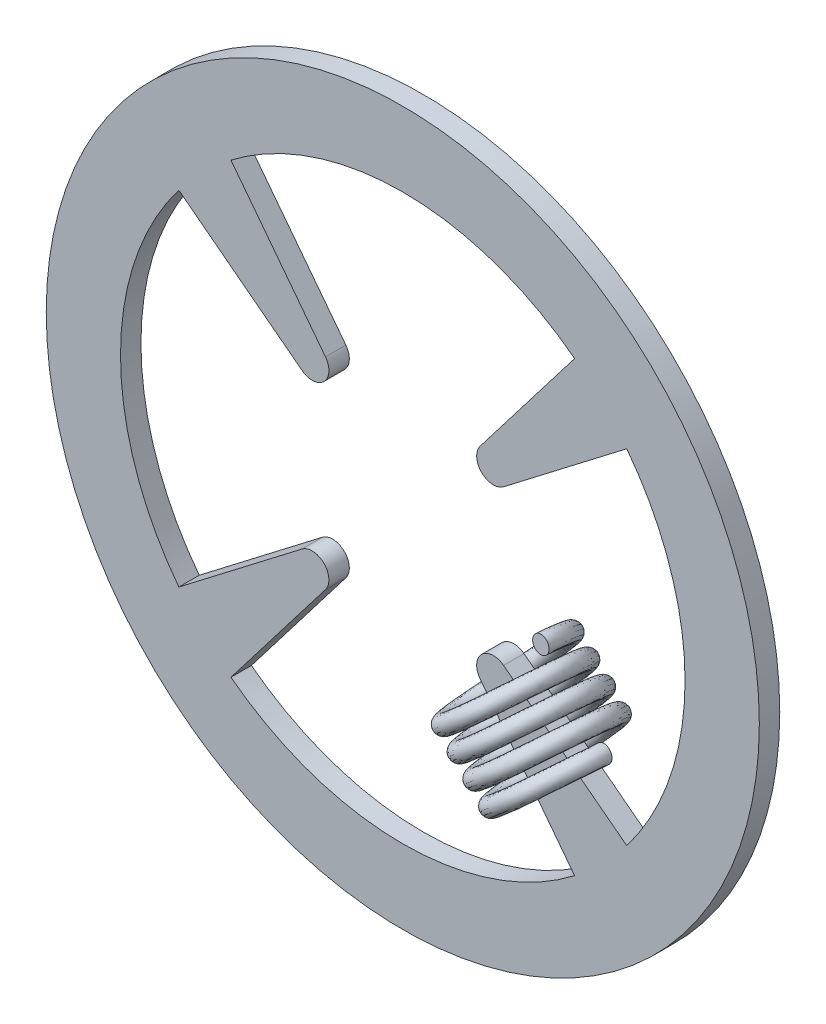
SolidWorks part; units mm, degrees
other "標示1"
sketch "草圖65"
ref_plane "前基準面" through (0, 0, 0) normal (0, 0, 1) x (1, 0, 0)
ref_plane "上基準面" through (0, 0, 0) normal (0, 1, 0) x (1, 0, 0)
ref_plane "右基準面" through (0, 0, 0) normal (1, 0, 0) x (0, 0, -1)
sketch "草圖1" plane through (0, 0, 0) normal (0, 0, 1) x (1, 0, 0)
  circle A0 centre (0, 0) radius 0.96
  circle A1 centre (0, 0) radius 0.76
extrude "填料-伸長1" add sketch "草圖1" along normal blind 0.055
sketch "草圖2" plane through (0, 0, 0.055) normal (0, 0, 1) x (1, 0, 0)
  line L0 (0, 0) -> (0, 1.565) construction
  line L1 (0, 0) -> (-1.8584, 0) construction
  line L2 (-0.0447, 0.3392) -> (-0.0992, 0.7535)
  line L3 (0.0447, 0.3392) -> (0.0992, 0.7535)
  line L4 (0.2714, 0.2082) -> (0.6029, 0.4627)
  line L5 (0.2082, 0.2714) -> (0.4627, 0.6029)
  line L6 (0.2082, -0.2714) -> (0.4627, -0.6029)
  line L7 (0.2714, -0.2082) -> (0.6029, -0.4627)
  line L8 (-0.2714, -0.2082) -> (-0.6029, -0.4627)
  line L9 (-0.2082, -0.2714) -> (-0.4627, -0.6029)
  line L10 (-0.2082, 0.2714) -> (-0.4627, 0.6029)
  line L11 (-0.2714, 0.2082) -> (-0.6029, 0.4627)
  circle A0 centre (0, 0) radius 0.3
  circle A1 centre (0, 0) radius 0.76 construction
  arc A3 (-0.0447, 0.3392) -> (0.0447, 0.3392) centre (0, 0.345) ccw
  arc A4 (0.0992, 0.7535) -> (-0.0992, 0.7535) centre (0, 0) ccw
  arc A5 (-0.76, 0) -> (0.76, 0) centre (0, 0) ccw
  arc A6 (0.6029, 0.4627) -> (0.4627, 0.6029) centre (0, 0) ccw
  arc A7 (0.2082, 0.2714) -> (0.2714, 0.2082) centre (0.244, 0.244) ccw
  arc A8 (0.4627, -0.6029) -> (0.6029, -0.4627) centre (0, 0) ccw
  arc A9 (0.2714, -0.2082) -> (0.2082, -0.2714) centre (0.244, -0.244) ccw
  arc A10 (-0.6029, -0.4627) -> (-0.4627, -0.6029) centre (0, 0) ccw
  arc A11 (-0.2082, -0.2714) -> (-0.2714, -0.2082) centre (-0.244, -0.244) ccw
  arc A12 (-0.4627, 0.6029) -> (-0.6029, 0.4627) centre (0, 0) ccw
  arc A13 (-0.2714, 0.2082) -> (-0.2082, 0.2714) centre (-0.244, 0.244) ccw
  point P23 (0, 0)
  point P34 (0, 0)
  point P41 (0, 0)
  circle M4 centre (0, 0) radius 0.76
  dimension "D1" = 7.5
  dimension "D3" = 2
  dimension "D4" = 4
  dimension "D2" = 7.5
extrude "填料-伸長2" add sketch "草圖2" against normal blind 0.055 contours L11 A13 L10 M4 | L5 A7 L4 M4 | L7 A9 L6 M4 | A11 L8 L9 M4
sketch "草圖7" plane through (0, 0, 0.055) normal (0, 0, 1) x (1, 0, 0)
  line L0 (0.2121, 0.2121) -> (0.2404, 0.2404) construction
  line L1 (0.2404, 0.2404) -> (0.2013, 0.2795) construction
  line L2 (0.2404, 0.2404) -> (0.5894, 0.5894) construction
  line L3 (0.0244, -0.0244) -> (-0.6648, 0.6648) construction
  line L4 (0.2404, -0.2404) -> (0.3328, -0.148)
  arc A0 (0.2082, 0.2714) -> (0.2714, 0.2082) centre (0.244, 0.244) ccw construction
  arc A1 (-0.2082, -0.2714) -> (-0.2714, -0.2082) centre (-0.244, -0.244) ccw construction
  arc A2 (-0.2714, 0.2082) -> (-0.2082, 0.2714) centre (-0.244, 0.244) ccw construction
  arc A3 (0.2714, -0.2082) -> (0.2082, -0.2714) centre (0.244, -0.244) ccw construction
  point P5 (0.297, 0.297)
  point P7 (-0.2121, -0.2121)
  point P8 (0.3536, 0.3536)
  point P9 (0.4101, 0.4101)
  point P12 (-0.2404, -0.2404)
  point P16 (-0.297, -0.297)
  point P17 (-0.3536, -0.3536)
  point P18 (-0.4101, -0.4101)
  point P20 (0.2404, -0.2404)
  point P21 (0, 0)
  point P23 (-0.2404, 0.2404)
  point P24 (-0.2121, 0.2121)
  point P25 (0.2121, -0.2121)
  point P29 (0.297, -0.297)
  point P33 (0.3536, -0.3536)
  point P34 (0.4101, -0.4101)
  point P35 (-0.297, 0.297)
  point P36 (-0.3536, 0.3536)
  point P37 (-0.4101, 0.4101)
  point P40 (0.4667, -0.4667)
  point P41 (0.5233, -0.5233)
  point P42 (0.4667, 0.4667)
  point P43 (0.5233, 0.5233)
  point P44 (-0.4667, 0.4667)
  point P45 (-0.5233, 0.5233)
  point P46 (-0.4667, -0.4667)
  point P47 (-0.5233, -0.5233)
  dimension "D1" = 0.08
  dimension "D2" = 0.08
  dimension "D3" = 0.08
  dimension "D4" = 0.04
  dimension "D5" = 0.04
  dimension "D6" = 0.08
  dimension "D7" = 0.08
  dimension "D8" = 0.08
  dimension "D9" = 0.04
  dimension "D10" = 0.04
  dimension "D11" = 0.08
  dimension "D12" = 0.08
  dimension "D13" = 0.08
  dimension "D14" = 0.08
  dimension "D15" = 0.08
  dimension "D16" = 0.08
  dimension "D17" = 0.08
  dimension "D18" = 0.08
  dimension "D19" = 0.08
  dimension "D20" = 0.08
  dimension "D21" = 0.08
  dimension "D22" = 0.08
  dimension "D23" = 0.08
  dimension "D24" = 0.08
ref_plane "平面5" through (0.2404, 0.2404, 0) normal (0.7071, 0.7071, 0) x (-0.7071, 0.7071, 0)
ref_plane "平面6" through (0.297, 0.297, 0) normal (0.7071, 0.7071, 0) x (0.7071, -0.7071, 0)
ref_plane "平面7" through (0.3536, 0.3536, 0) normal (0.7071, 0.7071, 0) x (0.7071, -0.7071, 0)
ref_plane "平面8" through (0.4101, 0.4101, 0) normal (0.7071, 0.7071, 0) x (0.7071, -0.7071, 0)
ref_plane "平面9" through (-0.2404, -0.2404, 0) normal (0.7071, 0.7071, 0) x (0.7071, -0.7071, 0)
ref_plane "平面10" through (-0.297, -0.297, 0) normal (0.7071, 0.7071, 0) x (0.7071, -0.7071, 0)
ref_plane "平面11" through (-0.3536, -0.3536, 0) normal (0.7071, 0.7071, 0) x (0.7071, -0.7071, 0)
ref_plane "平面12" through (-0.4101, -0.4101, 0) normal (0.7071, 0.7071, 0) x (0.7071, -0.7071, 0)
ref_plane "平面13" through (0.2404, -0.2404, 0) normal (0.7071, -0.7071, 0) x (0.7071, 0.7071, 0)
ref_plane "平面14" through (0.297, -0.297, 0) normal (0.7071, -0.7071, 0) x (0, 0, -1)
ref_plane "平面15" through (0.3536, -0.3536, 0) normal (0.7071, -0.7071, 0) x (0, 0, -1)
ref_plane "平面16" through (0.4101, -0.4101, 0) normal (0.7071, -0.7071, 0) x (0, 0, -1)
ref_plane "平面17" through (-0.2404, 0.2404, 0) normal (0.7071, -0.7071, 0) x (0, 0, -1)
ref_plane "平面18" through (-0.297, 0.297, 0) normal (0.7071, -0.7071, 0) x (0, 0, -1)
ref_plane "平面19" through (-0.3536, 0.3536, 0) normal (0.7071, -0.7071, 0) x (0, 0, -1)
ref_plane "平面20" through (-0.4101, 0.4101, 0) normal (0.7071, -0.7071, 0) x (0, 0, -1)
ref_plane "平面21" through (0, 0, 0) normal (-0.7071, -0.7071, 0) x (-0.7071, 0.7071, 0)
sketch "草圖68" plane through (0, 0, 0) normal (-0.7071, -0.7071, 0) x (-0.7071, 0.7071, 0)
  line L0 (-0.34, -0.0851) -> (-0.34, -0.3432)
  line L1 (-200000.0345, -0.055) -> (200000.9402, -0.055) construction
  circle A0 centre (-0.34, 0.025) radius 0.023
  point P1 (-0.34, 0.025)
  dimension "D1" = 0.08
sketch "草圖69" plane through (0.2404, -0.2404, 0) normal (0.7071, -0.7071, 0) x (0.7071, 0.7071, 0)
  line L0 (0, -199999.9149) -> (0, 200000.3432) construction
  circle A0 centre (0, 0.03) radius 0.15
  point P0 (0, 0.03)
  dimension "D1" = 0.025
curve "螺旋曲線/渦捲線1" pitch 0.06 height 0.24 turns 4
ref_plane "平面23" through (0.5162, -0.3041, 0.03) normal (0.0449, -0.0449, -0.998) x (-0.999, -0.0033, -0.0448)
sketch "草圖71" plane through (0.5162, -0.3041, 0.03) normal (0.0449, -0.0449, -0.998) x (-0.999, -0.0033, -0.0448)
  circle A0 centre (-0.0002, 0.0001) radius 0.023
sweep "掃出1" add profiles "草圖71" path "螺旋曲線/渦捲線1"
